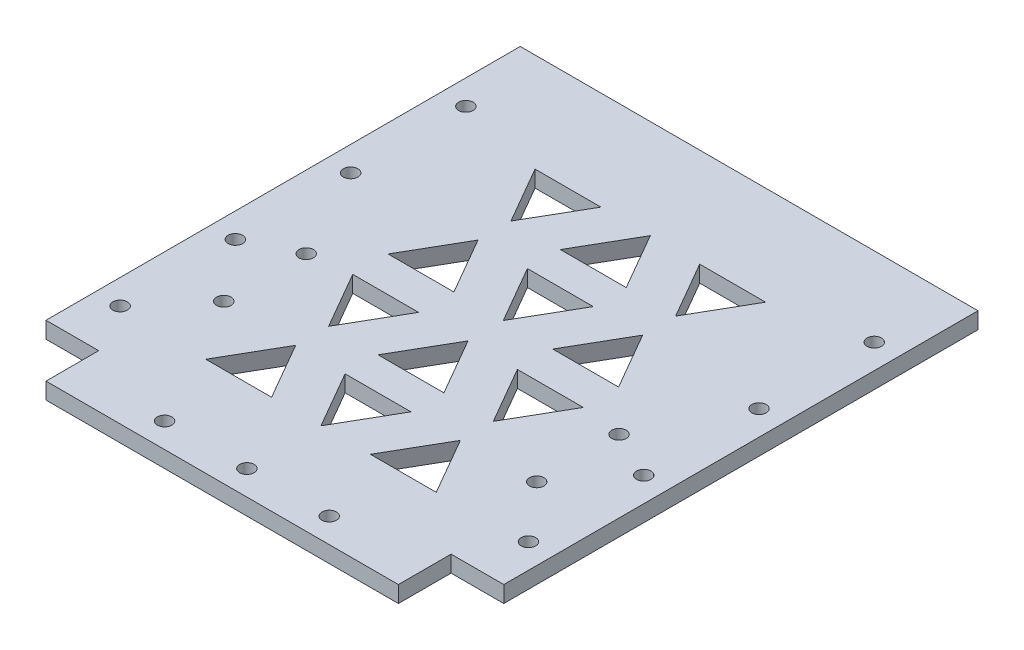
SolidWorks part; units mm, degrees
other "Markup1"
sketch "Sketch7" plane through (-69.5, 3, -80) normal (0, 1, 0) x (1, 0, 0)
ref_plane "Front Plane" through (0, 0, 0) normal (0, 0, 1) x (1, 0, 0)
ref_plane "Top Plane" through (0, 0, 0) normal (0, 1, 0) x (1, 0, 0)
ref_plane "Right Plane" through (0, 0, 0) normal (1, 0, 0) x (0, 0, -1)
sketch "Sketch1" plane through (0, 0, 0) normal (0, 1, 0) x (1, 0, 0)
  line L1 (-69.5, 80) -> (69.5, 80)
  line L2 (-69.5, 80) -> (-69.5, -80)
  line L3 (-69.5, -80) -> (69.5, -80)
  line L4 (69.5, 80) -> (69.5, -80)
  line L5 (-69.5, 80) -> (69.5, -80) construction
  line L6 (-69.5, -80) -> (69.5, 80) construction
  point P0 (0, 0)
  dimension "D1" = 160
  dimension "D2" = 139
extrude "Boss-Extrude1" add sketch "Sketch1" along normal blind 5
sketch "Sketch2" plane through (0, 5, 0) normal (0, 1, 0) x (1, 0, 0)
  line L1 (-69.5, -80) -> (-53.5, -80)
  line L2 (-69.5, -80) -> (-69.5, -64)
  line L3 (-69.5, -64) -> (-53.5, -64)
  line L4 (-53.5, -80) -> (-53.5, -64)
  dimension "D1" = 16
  dimension "D2" = 16
extrude "Cut-Extrude1" cut sketch "Sketch2" against normal through all
mirror "Mirror1" about plane through (0, 0, 0) normal (1, 0, 0) of "Cut-Extrude1"
sketch "Sketch3" plane through (0, 5, 0) normal (0, 1, 0) x (1, 0, 0)
  line L0 (0, -2.75) -> (0, 2.75) construction
  line L1 (-53.5, -80) -> (53.5, -80) construction
  circle A0 centre (0, -72.5) radius 2.2
  circle A1 centre (-25, -72.5) radius 2.2
  circle A2 centre (25, -72.5) radius 2.2
  dimension "D1" = 4.4
  dimension "D2" = 4.4
  dimension "D3" = 4.4
  dimension "D4" = 25
  dimension "D5" = 25
  dimension "D6" = 7.5
extrude "Cut-Extrude2" cut sketch "Sketch3" against normal through all
sketch "Sketch4" plane through (0, 5, 0) normal (0, 1, 0) x (1, 0, 0)
  line L0 (-53.5, -64) -> (-69.5, -64) construction
  line L1 (-69.5, 80) -> (-69.5, -64) construction
  circle A0 centre (-62, -49) radius 2.2
  dimension "D3" = 4.4
  dimension "D1" = 15
  dimension "D2" = 7.5
extrude "Cut-Extrude3" cut sketch "Sketch4" against normal through all
pattern_linear "LPattern1" count 4 spacing 35 along (0, 0, -1) of "Cut-Extrude3"
mirror "Mirror2" about plane through (0, 0, 0) normal (1, 0, 0) of "LPattern1", "Cut-Extrude3"
sketch "Sketch5" plane through (0, 5, 0) normal (0, 1, 0) x (1, 0, 0)
  line L0 (0, -2.75) -> (0, 2.75) construction
  line L1 (-53.5, -80) -> (53.5, -80) construction
  circle A0 centre (-47.5, -32) radius 2.2
  circle A1 centre (-47.5, -7) radius 2.2
  dimension "D4" = 4.4
  dimension "D5" = 4.4
  dimension "D1" = 47.5
  dimension "D2" = 47.5
  dimension "D3" = 25
  dimension "D6" = 48
extrude "Cut-Extrude4" cut sketch "Sketch5" against normal through all
mirror "Mirror3" about plane through (0, 0, 0) normal (1, 0, 0) of "Cut-Extrude4"
sketch "Sketch6" plane through (0, 5, 0) normal (0, 1, 0) x (1, 0, 0)
  line L0 (0, 50) -> (-10, 32.6795)
  line L3 (0, -2.75) -> (0, 2.75) construction
  line L8 (-10, 32.6795) -> (10, 32.6795)
  line L9 (10, 32.6795) -> (0, 50)
  line L10 (69.5, 80) -> (-69.5, 80) construction
  line L11 (15, 50) -> (25, 32.6795)
  line L12 (25, 32.6795) -> (35, 50)
  line L13 (35, 50) -> (15, 50)
  line L15 (-25, 32.6795) -> (-35, 50)
  line L16 (-15, 50) -> (-25, 32.6795)
  line L17 (-35, 50) -> (-15, 50)
  line L18 (0, 27.6795) -> (-71.171, 27.6795) construction
  line L19 (25, 22.6795) -> (35, 5.359)
  line L20 (15, 5.359) -> (25, 22.6795)
  line L21 (35, 5.359) -> (15, 5.359)
  line L22 (-10, 22.6795) -> (10, 22.6795)
  line L23 (0, 5.359) -> (-10, 22.6795)
  line L24 (10, 22.6795) -> (0, 5.359)
  line L25 (-15, 5.359) -> (-25, 22.6795)
  line L26 (-35, 5.359) -> (-15, 5.359)
  line L27 (-25, 22.6795) -> (-35, 5.359)
  line L28 (-2.75, 0) -> (2.75, 0) construction
  line L29 (15, -5.359) -> (25, -22.6795)
  line L30 (35, -5.359) -> (15, -5.359)
  line L31 (25, -22.6795) -> (35, -5.359)
  line L32 (0, -5.359) -> (-10, -22.6795)
  line L33 (10, -22.6795) -> (0, -5.359)
  line L34 (-10, -22.6795) -> (10, -22.6795)
  line L35 (-35, -5.359) -> (-15, -5.359)
  line L36 (-25, -22.6795) -> (-35, -5.359)
  line L37 (-15, -5.359) -> (-25, -22.6795)
  line L38 (25, -32.6795) -> (35, -50)
  line L39 (15, -50) -> (25, -32.6795)
  line L40 (35, -50) -> (15, -50)
  line L41 (-10, -32.6795) -> (10, -32.6795)
  line L42 (0, -50) -> (-10, -32.6795)
  line L43 (10, -32.6795) -> (0, -50)
  line L44 (-15, -50) -> (-25, -32.6795)
  line L45 (-35, -50) -> (-15, -50)
  line L46 (-25, -32.6795) -> (-35, -50)
  point P0 (0, 32.6795)
  point P9 (0, 41.3108)
  dimension "D1" = 20
  dimension "D2" = 0
  dimension "D3" = 20
  dimension "D4" = 20
  dimension "D5" = 30
  dimension "D6" = 20
  dimension "D7" = 20
  dimension "D8" = 20
  dimension "D9" = 15
  dimension "D10" = 5
extrude "Cut-Extrude5" cut sketch "Sketch6" against normal through all
equation "\"D3@Sketch3\"=\"D1@Sketch3\""
equation "\"D2@Sketch3\"=\"D1@Sketch3\""
equation "\"D2@Sketch5\"=\"D1@Sketch5\""
